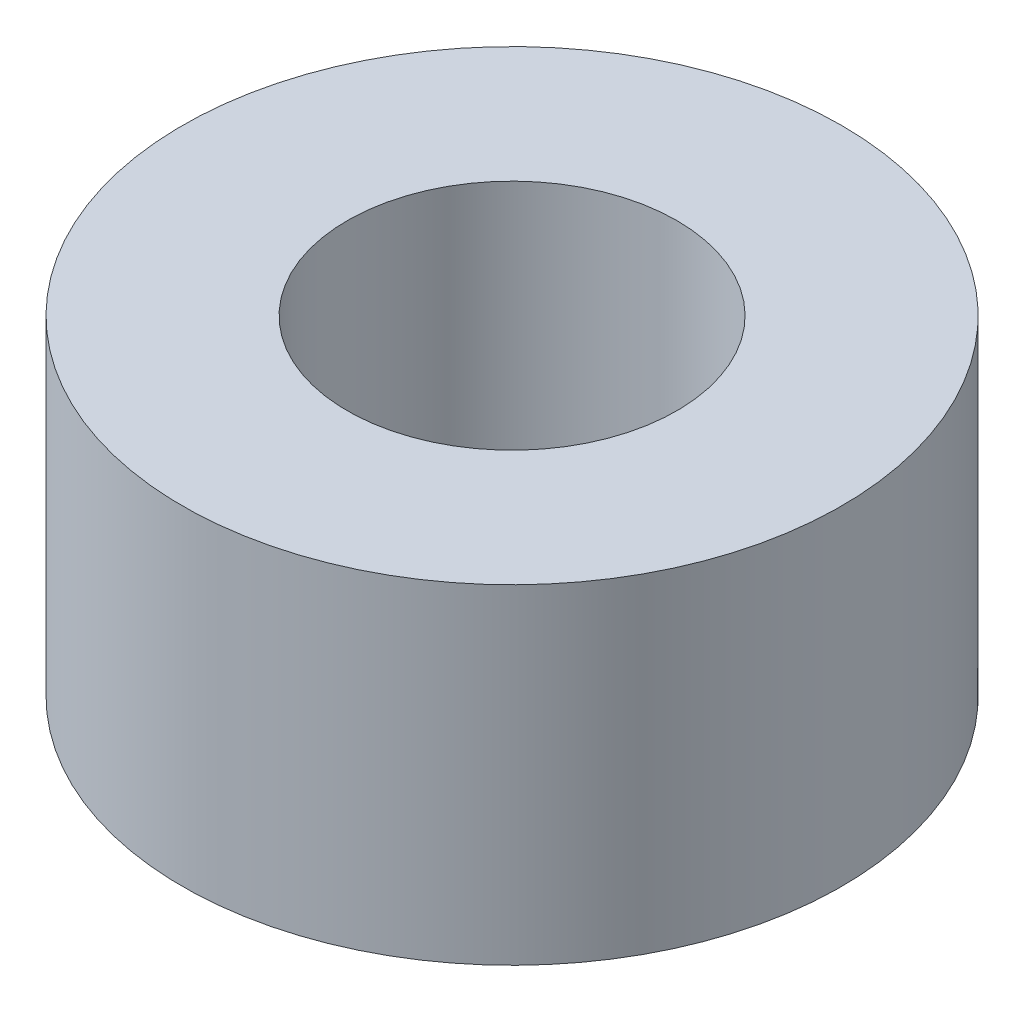
SolidWorks part; units mm, degrees
material "ABS"
ref_plane "Front Plane" through (0, 0, 0) normal (0, 0, 1) x (1, 0, 0)
ref_plane "Top Plane" through (0, 0, 0) normal (0, 1, 0) x (1, 0, 0)
ref_plane "Right Plane" through (0, 0, 0) normal (1, 0, 0) x (0, 0, -1)
sketch "Sketch1" plane through (0, 0, 0) normal (0, 1, 0) x (1, 0, 0)
  circle A0 centre (0, 0) radius 9.525
  circle A1 centre (0, 0) radius 4.7625
  dimension "D1" = 9.525
  dimension "D2" = 19.05
extrude "Boss-Extrude1" add sketch "Sketch1" along normal blind 9.525
equation "\"ID\"=0.779725"
equation "\"OD\"=0.75"
equation "\"D2@Sketch1\"=\"OD\""
